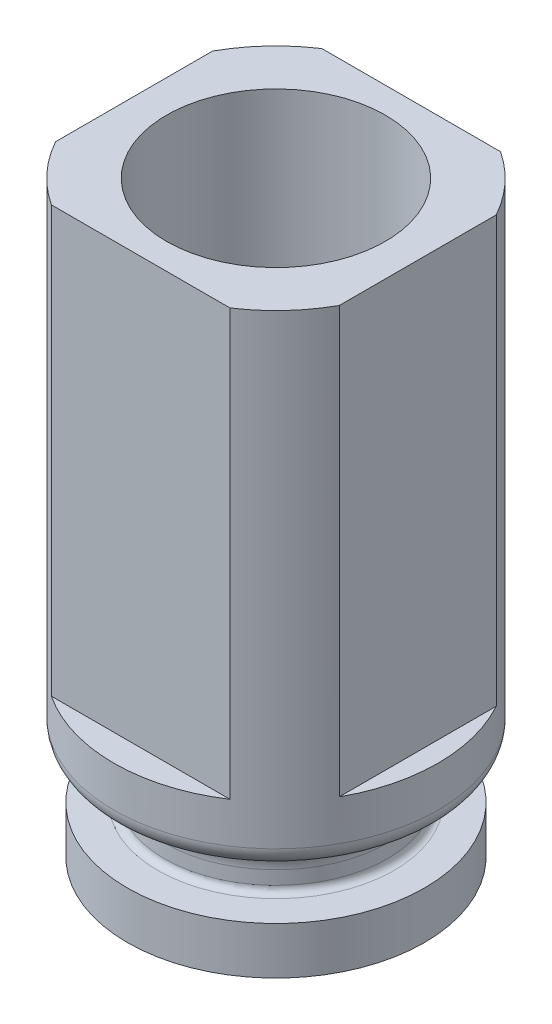
SolidWorks part; units mm, degrees
ref_plane "Спереди" through (0, 0, 0) normal (0, 0, 1) x (1, 0, 0)
ref_plane "Сверху" through (0, 0, 0) normal (0, 1, 0) x (1, 0, 0)
ref_plane "Справа" through (0, 0, 0) normal (1, 0, 0) x (0, 0, -1)
sketch "Эскиз1" plane through (0, 0, 0) normal (0, 1, 0) x (1, 0, 0)
  circle A1 centre (0, 0) radius 22
  dimension "D1" = 44
extrude "Вытянуть1" add sketch "Эскиз1" along normal blind 15
sketch "Эскиз2" plane through (0, 0, 0) normal (0, -1, 0) x (1, 0, 0)
  circle A0 centre (0, 0) radius 14.5
  dimension "D1" = 29
extrude "Вытянуть2" cut sketch "Эскиз2" against normal blind 6.5
sketch "Эскиз4" plane through (0, 15, 0) normal (0, 1, 0) x (1, 0, 0)
  circle A0 centre (0, 0) radius 16.5
  circle A1 centre (0, 0) radius 25
extrude "Вырез-Вытянуть1" cut sketch "Эскиз4" against normal blind 8
sketch "Эскиз5" plane through (0, 15, 0) normal (0, 1, 0) x (1, 0, 0)
  circle A0 centre (0, 0) radius 16.2
  circle A1 centre (0, 0) radius 24
extrude "Вытянуть4" add sketch "Эскиз5" along normal blind 72
fillet "Скругление1" radius 1 1 edges at (0, 7, 16.5)
fillet "Скругление2" radius 5 1 edges at (0, 15, 16.5)
fillet "Скругление3" radius 3 1 edges at (0, 15, 24)
sketch "Эскиз6" plane through (0, 0, 0) normal (0, 1, 0) x (1, 0, 0)
  line L0 (0, 0) -> (0, 31.4434) construction
  line L1 (21, 20.0323) -> (21, -20.0323)
  line L2 (21, 29.7019) -> (36.4259, 29.7019)
  line L3 (36.4259, 29.7019) -> (36.4259, -29.5227)
  line L4 (-36.4259, -29.5227) -> (36.4259, -29.5227)
  line L5 (-21, 20.0323) -> (-21, -20.0323)
  line L7 (-36.4259, 29.7019) -> (-36.4259, -29.5227)
  line L8 (-21, 29.7019) -> (-36.4259, 29.7019)
  line L9 (-21, 20.0323) -> (21, 20.0323)
  line L10 (-21, 29.7019) -> (21, 29.7019)
  line L11 (0, 0) -> (-51.0959, 0) construction
  line L12 (-21, -20.0323) -> (21, -20.0323)
  dimension "D1" = 42
extrude "Вырез-Вытянуть2" cut sketch "Эскиз6" along normal blind 50 and the other way blind 26 from offset 50
sketch "Эскиз7" plane through (0, 0, 0) normal (0, 0, 1) x (1, 0, 0)
  line L0 (0, 87) -> (0, 57.4012) construction
